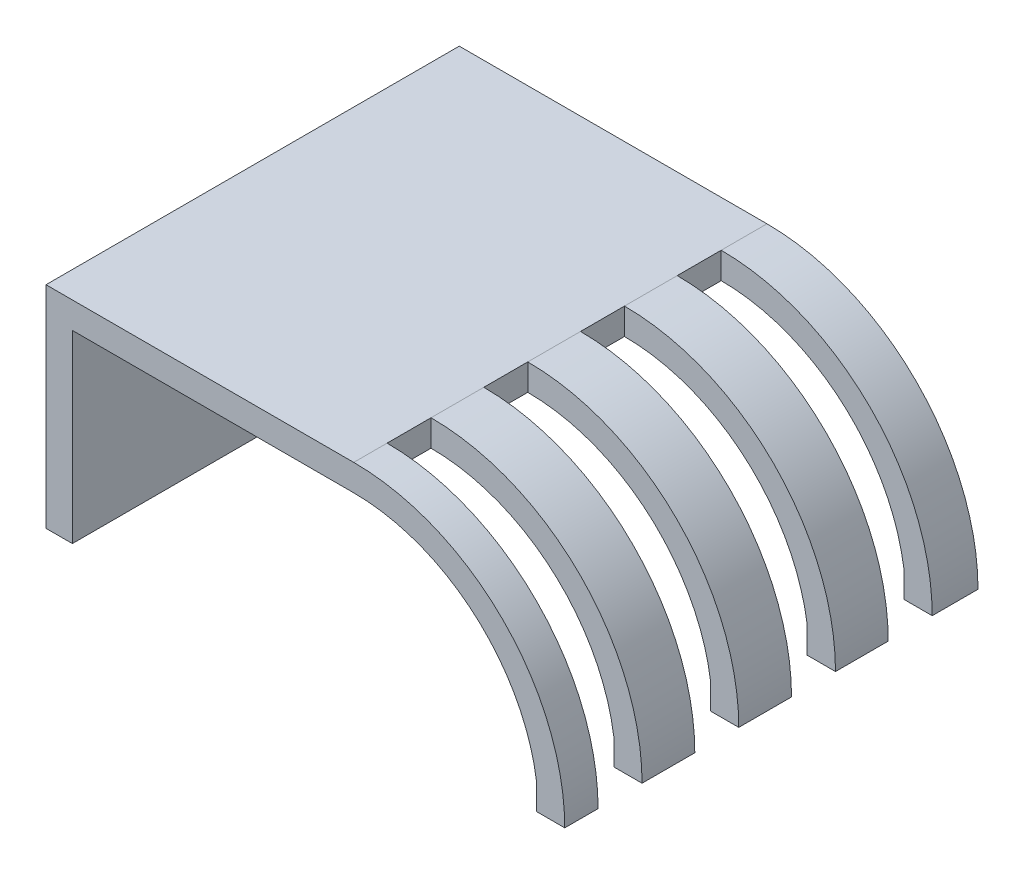
SolidWorks part; units mm, degrees
ref_plane "Front Plane" through (0, 0, 0) normal (0, 0, 1) x (1, 0, 0)
ref_plane "Top Plane" through (0, 0, 0) normal (0, 1, 0) x (1, 0, 0)
ref_plane "Right Plane" through (0, 0, 0) normal (1, 0, 0) x (0, 0, -1)
sketch "Sketch1" plane through (0, 0, 0) normal (0, 1, 0) x (1, 0, 0)
  line L1 (-17.5, 11.75) -> (17.5, 11.75)
  line L2 (-17.5, 11.75) -> (-17.5, -11.75)
  line L3 (-17.5, -11.75) -> (17.5, -11.75)
  line L4 (17.5, 11.75) -> (17.5, -11.75)
  line L5 (-17.5, 11.75) -> (17.5, -11.75) construction
  line L6 (-17.5, -11.75) -> (17.5, 11.75) construction
  point P0 (0, 0)
  dimension "D1" = 35
  dimension "D2" = 23.5
extrude "Boss-Extrude1" add sketch "Sketch1" along normal blind 12
sketch "Sketch3" plane through (0, 0, 11.75) normal (0, 0, 1) x (1, 0, 0)
  line L0 (-17.5, 12) -> (-11.8409, 12)
  line L1 (-17.5, 12) -> (17.5, 12) construction
  line L2 (-17.5, 12) -> (-11.8409, 12)
  line L4 (-11.8409, 12) -> (-17.5, 12)
  line L7 (-17.5, 0) -> (17.5, 0)
  line L8 (17.5, 0) -> (17.5, 12)
  line L9 (17.5, 12) -> (-17.5, 12)
  line L10 (-17.5, 12) -> (-17.5, 0)
  line L11 (-17.5, 0) -> (17.5, 0)
  line L17 (0, 12) -> (17.5, 12)
  line L18 (17.5, 12) -> (17.5, 0)
  arc A0 (12, 0) -> (0, 12) centre (0, 0) ccw
  line M6 (17.5, 0) -> (17.5, 12)
  line M7 (17.5, 12) -> (-17.5, 12)
  dimension "D1" = 0
extrude "Cut-Extrude1" cut sketch "Sketch3" against normal through all contours A0 L11 M6 M7
sketch "Sketch4" plane through (0, 0, 11.75) normal (0, 0, 1) x (1, 0, 0)
  line L3 (0, 12) -> (-17.5, 12)
  line L4 (-17.5, 12) -> (-17.5, 0)
  line L5 (-17.5, 0) -> (12, 0)
  line L6 (0, 12) -> (-17.5, 12)
  line L7 (-17.5, 12) -> (-17.5, 0)
  line L8 (-17.5, 0) -> (12, 0)
  line L12 (0, 10.5) -> (-16, 10.5)
  line L13 (-16, 10.5) -> (-16, 1.5)
  line L14 (-16, 1.5) -> (10.3923, 1.5)
  line L15 (0, 10.5) -> (-16, 10.5)
  line L16 (-16, 10.5) -> (-16, 1.5)
  line L17 (-16, 1.5) -> (10.3923, 1.5)
  arc A1 (12, 0) -> (0, 12) centre (0, 0) ccw
  arc A2 (12, 0) -> (0, 12) centre (0, 0) ccw
  arc A4 (10.3923, 1.5) -> (0, 10.5) centre (0, 0) ccw
  arc A5 (10.3923, 1.5) -> (0, 10.5) centre (0, 0) ccw
  dimension "D1" = 0
  dimension "D2" = 1.5
extrude "Cut-Extrude2" cut sketch "Sketch4" against normal through all contours L17 A5 L15 L16
sketch "Sketch5" plane through (0, 1.5, 0) normal (0, 1, 0) x (1, 0, 0)
  line L1 (-16, 11.75) -> (10.3923, 11.75)
  line L2 (-16, 11.75) -> (-16, -11.75)
  line L3 (-16, -11.75) -> (10.3923, -11.75)
  line L4 (10.3923, 11.75) -> (10.3923, -11.75)
extrude "Cut-Extrude3" cut sketch "Sketch5" against normal blind 12
sketch "Sketch6" plane through (0, 12, 0) normal (0, 1, 0) x (1, 0, 0)
  line L0 (0, 11.75) -> (0, -11.75) construction
  line L1 (0, -9.8542) -> (14.7867, -9.8542)
  line L2 (0, -9.8542) -> (0, -7.3542)
  line L3 (0, -7.3542) -> (14.7867, -7.3542)
  line L4 (14.7867, -9.8542) -> (14.7867, -7.3542)
  line L5 (0, -1.8542) -> (14.7867, -1.8542)
  line L6 (0, -4.3542) -> (14.7867, -4.3542)
  line L7 (14.7867, -4.3542) -> (14.7867, -1.8542)
  line L8 (0, -4.3542) -> (0, -1.8542)
  line L9 (0, 3.6458) -> (14.7867, 3.6458)
  line L10 (0, 1.1458) -> (14.7867, 1.1458)
  line L11 (14.7867, 1.1458) -> (14.7867, 3.6458)
  line L12 (0, 1.1458) -> (0, 3.6458)
  line L13 (0, 9.1458) -> (14.7867, 9.1458)
  line L14 (0, 6.6458) -> (14.7867, 6.6458)
  line L15 (14.7867, 6.6458) -> (14.7867, 9.1458)
  line L16 (0, 6.6458) -> (0, 9.1458)
  dimension "D1" = 2.5
  dimension "D2" = 4
extrude "Cut-Extrude4" cut sketch "Sketch6" against normal through all
